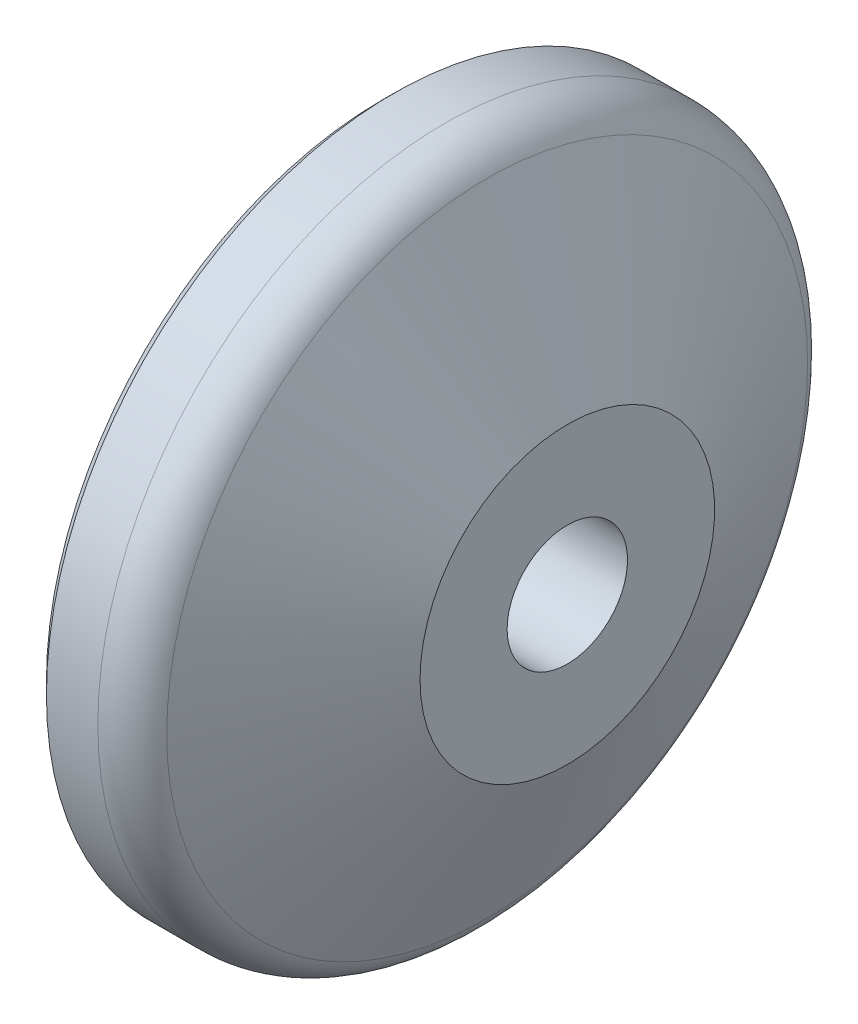
SolidWorks part; units mm, degrees
material "1023 Carbon Steel Sheet (SS)"
ref_plane "Front Plane" through (0, 0, 0) normal (0, 0, 1) x (1, 0, 0)
ref_plane "Top Plane" through (0, 0, 0) normal (0, 1, 0) x (1, 0, 0)
ref_plane "Right Plane" through (0, 0, 0) normal (1, 0, 0) x (0, 0, -1)
sketch "Sketch1" plane through (0, 0, 0) normal (0, 0, 1) x (1, 0, 0)
  line L0 (0, 0) -> (12.218, 0) construction
  line L1 (0, 4) -> (0, 15)
  line L2 (0, 15) -> (4, 15)
  line L3 (4, 15) -> (8, 6.3629)
  line L4 (8, 6.3629) -> (8, 2.6)
  line L5 (8, 2.6) -> (4, 2.6)
  line L6 (4, 2.6) -> (4, 4)
  line L7 (4, 4) -> (0, 4)
  point P5 (8, 6.3629)
  dimension "D1" = 11
  dimension "D2" = 4
  dimension "D3" = 1.4
  dimension "D4" = 4
  dimension "D5" = 4
  dimension "D6" = 4
revolve "Revolve1" add sketch "Sketch1" angle 360 about L0
fillet "Fillet1" radius 2 1 edges at (4, 0, 15)
chamfer "Chamfer1" distance 0.5 angle 45 2 edges at (0, 0, 4) (0, 0, 15)
